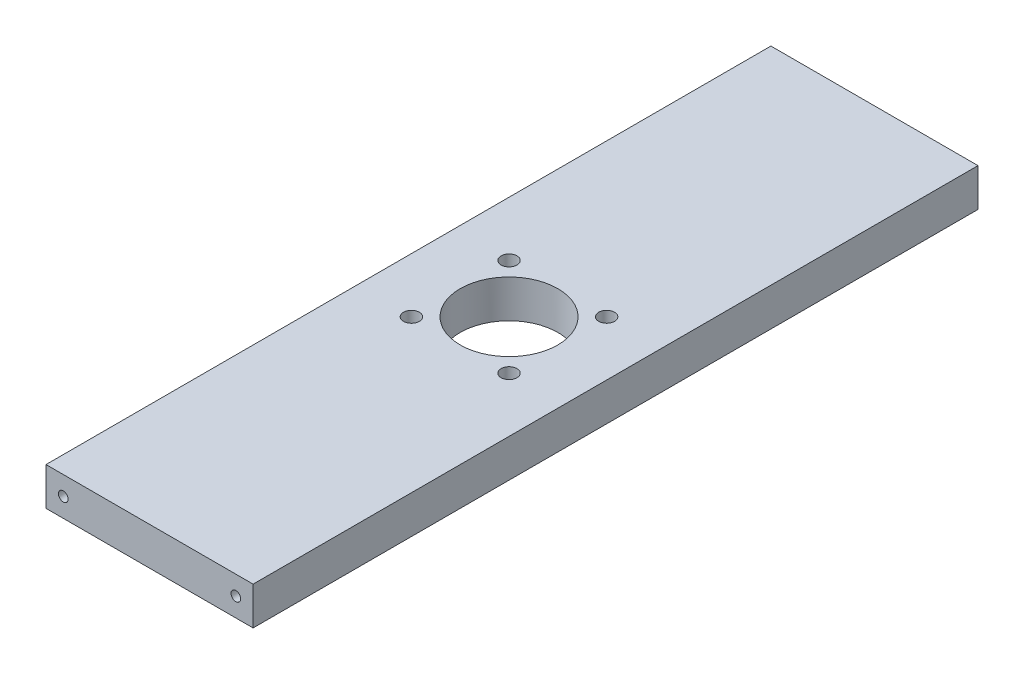
SolidWorks part; units mm, degrees
ref_plane "Ön Düzlem" through (0, 0, 0) normal (0, 0, 1) x (1, 0, 0)
ref_plane "Üst Düzlem" through (0, 0, 0) normal (0, 1, 0) x (1, 0, 0)
ref_plane "Sağ Düzlem" through (0, 0, 0) normal (1, 0, 0) x (0, 0, -1)
sketch "Çizim1" plane through (0, 0, 0) normal (0, 0, 1) x (1, 0, 0)
  line L0 (-39.267, 0) -> (40.7374, 0) construction
  line L1 (0, 36.3097) -> (0, -28.9247) construction
  line L2 (-26.1381, 10.0518) -> (33.8619, 10.0518)
  line L3 (33.8619, 10.0518) -> (33.8619, -0.9482)
  line L4 (-26.1381, 10.0518) -> (-26.1381, -0.9482)
  line L5 (-26.1381, -0.9482) -> (33.8619, -0.9482)
extrude "Yükseklik-Ekstrüzyon1" add sketch "Çizim1" along normal blind 210
sketch "Çizim2" plane through (0, 10.0518, 0) normal (0, 1, 0) x (1, 0, 0)
  circle A0 centre (3.8619, -105.86) radius 14.14
  circle A1 centre (-10.2781, -91.72) radius 2.3
  circle A2 centre (18.0019, -91.72) radius 2.3
  circle A3 centre (18.0019, -120) radius 2.3
  circle A4 centre (-10.2781, -120) radius 2.3
extrude "Kes-Ekstrüzyon1" cut sketch "Çizim2" against normal through all both and the other way through all
sketch "Çizim3" plane through (0, 0, 0) normal (0, 0, -1) x (-1, 0, 0)
  line L0 (26.1381, 4.5518) -> (21.1381, 4.5518) construction
  line L1 (26.1381, 10.0518) -> (26.1381, -0.9482) construction
  line L2 (-33.8619, 4.5518) -> (-28.8619, 4.5518) construction
  line L3 (-33.8619, -0.9482) -> (-33.8619, 10.0518) construction
  circle A0 centre (21.1381, 4.5518) radius 1.4
  circle A1 centre (-28.8619, 4.5518) radius 1.4
extrude "Kes-Ekstrüzyon2" cut sketch "Çizim3" against normal blind 21
sketch "Çizim4" plane through (0, 0, 210) normal (0, 0, 1) x (1, 0, 0)
  line L0 (-26.1381, 4.5518) -> (-21.1381, 4.5518) construction
  line L1 (-26.1381, 10.0518) -> (-26.1381, -0.9482) construction
  line L2 (33.8619, 4.5518) -> (28.8619, 4.5518) construction
  line L3 (33.8619, -0.9482) -> (33.8619, 10.0518) construction
  circle A0 centre (-21.1381, 4.5518) radius 1.4
  circle A1 centre (28.8619, 4.5518) radius 1.4
extrude "Kes-Ekstrüzyon3" cut sketch "Çizim4" against normal blind 21
